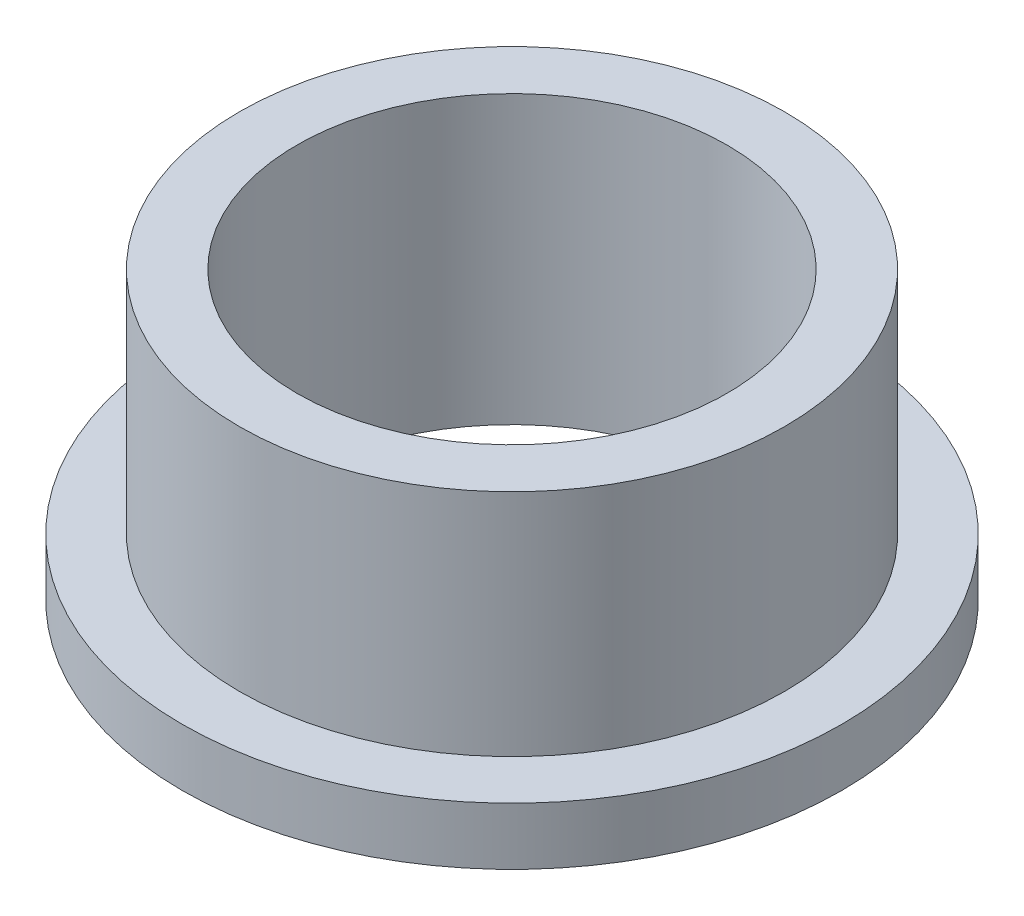
SolidWorks part; units mm, degrees
ref_plane "Front" through (0, 0, 0) normal (0, 0, 1) x (1, 0, 0)
ref_plane "Top" through (0, 0, 0) normal (0, 1, 0) x (1, 0, 0)
ref_plane "Right" through (0, 0, 0) normal (1, 0, 0) x (0, 0, -1)
sketch "Sketch1" plane through (0, 0, 0) normal (0, 1, 0) x (1, 0, 0)
  circle A0 centre (0, 0) radius 15.005
  circle A1 centre (0, 0) radius 19.02
  circle A2 centre (0, 0) radius 23
  dimension "ID" = 30.01
  dimension "OD" = 38.04
  dimension "FlangeOD" = 46
sketch "Sketch2" plane through (0, 0, 0) normal (0, 1, 0) x (1, 0, 0)
  circle A0 centre (0, 0) radius 15.005 construction
  circle A1 centre (0, 0) radius 19.02 construction
  circle A2 centre (0, 0) radius 15.005
  circle A3 centre (0, 0) radius 19.02
extrude "Boss-Extrude1" add sketch "Sketch2" along normal blind 20
sketch "Sketch3" plane through (0, 0, 0) normal (0, 1, 0) x (1, 0, 0)
  circle A0 centre (0, 0) radius 23 construction
  circle A1 centre (0, 0) radius 19.02 construction
  circle A2 centre (0, 0) radius 23
  circle A3 centre (0, 0) radius 19.02
extrude "Boss-Extrude2" add sketch "Sketch3" along normal blind 4
